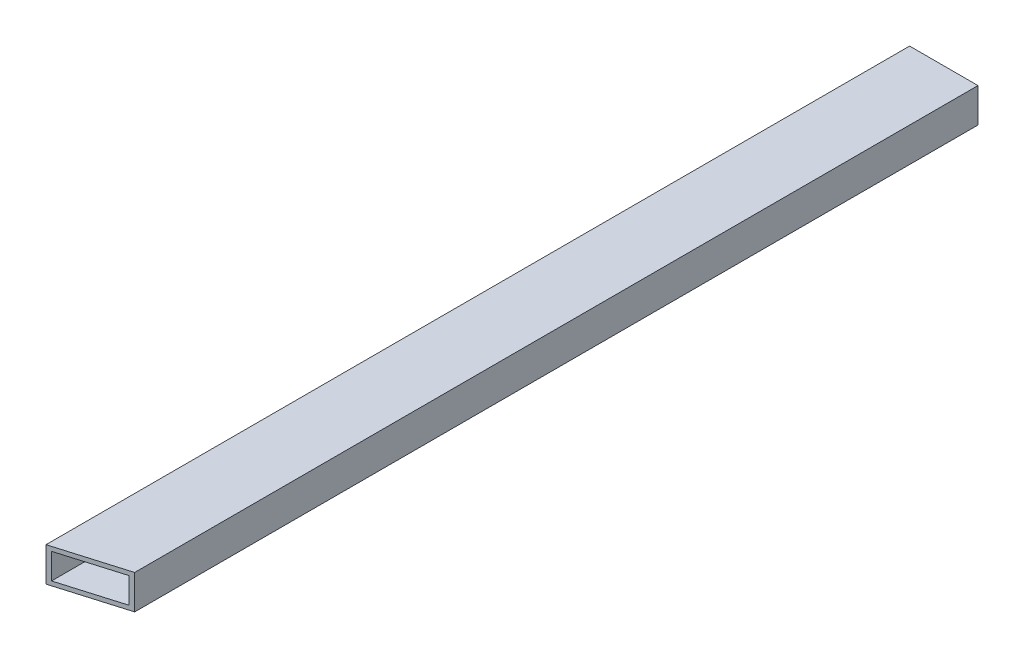
SolidWorks part; units mm, degrees
ref_plane "Front Plane" through (0, 0, 0) normal (0, 0, 1) x (1, 0, 0)
ref_plane "Top Plane" through (0, 0, 0) normal (0, 1, 0) x (1, 0, 0)
ref_plane "Right Plane" through (0, 0, 0) normal (1, 0, 0) x (0, 0, -1)
sketch "Sketch1" plane through (0, 0, 0) normal (0, 0, 1) x (1, 0, 0)
  line L0 (-22.225, 9.525) -> (22.225, 9.525)
  line L2 (-25.4, 12.7) -> (25.4, 12.7)
  line L3 (-25.4, 12.7) -> (-25.4, -12.7)
  line L4 (-25.4, -12.7) -> (25.4, -12.7)
  line L5 (25.4, 12.7) -> (25.4, -12.7)
  line L10 (22.225, 9.525) -> (22.225, -9.525)
  line L11 (-22.225, -9.525) -> (22.225, -9.525)
  line L12 (-22.225, 9.525) -> (-22.225, -9.525)
  point P12 (0, 12.7)
  point P14 (25.4, 0)
  dimension "Wall Thickness" = 3.175
  dimension "Outside Width" = 50.8
  dimension "Outside Height" = 25.4
  dimension "Inside Height" = 19.05
  dimension "Inside Width" = 44.45
sketch "Sketch2" plane through (0, 0, 0) normal (1, 0, 0) x (0, 0, -1)
  line L0 (320.675, 0) -> (-320.675, 0)
  point P4 (0, 0)
  point P7 (-320.675, 0)
  point P10 (320.675, 0)
  dimension "Length" = 641.35
sketch "Sketch3" plane through (0, 0, 0) normal (0, 0, 1) x (1, 0, 0)
  line L21 (25.4, 12.7) -> (-25.4, 12.7)
  line L22 (25.4, -12.7) -> (25.4, 12.7)
  line L23 (-25.4, -12.7) -> (25.4, -12.7)
  line L24 (-25.4, 12.7) -> (-25.4, -12.7)
  line L25 (25.4, 12.7) -> (-25.4, 12.7)
  line L26 (25.4, -12.7) -> (25.4, 12.7)
  line L27 (-25.4, -12.7) -> (25.4, -12.7)
  line L28 (-25.4, 12.7) -> (-25.4, -12.7)
  line L29 (22.225, 9.525) -> (-22.225, 9.525)
  line L30 (22.225, -9.525) -> (22.225, 9.525)
  line L31 (-22.225, -9.525) -> (22.225, -9.525)
  line L32 (-22.225, 9.525) -> (-22.225, -9.525)
  line L33 (22.225, 9.525) -> (-22.225, 9.525)
  line L34 (22.225, -9.525) -> (22.225, 9.525)
  line L35 (-22.225, -9.525) -> (22.225, -9.525)
  line L36 (-22.225, 9.525) -> (-22.225, -9.525)
  dimension "D1" = 0
  dimension "D2" = 0
extrude "Boss-Extrude1" add sketch "Sketch3" along normal up to vertex (320.675 mm away) and the other way up to vertex (320.675 mm away) up to point (0, 0, 320.675) other way up to point (0, 0, -320.675)
sketch "Drawing Reference" plane through (0, 0, 0) normal (1, 0, 0) x (0, 0, -1)
  line L0 (-320.675, 0) -> (320.675, 0) construction
  line L1 (0, -12.7) -> (0, 12.7) construction
  line L2 (-320.675, -12.7) -> (320.675, -12.7) construction
  line L5 (-320.675, 12.7) -> (320.675, 12.7) construction
  point P7 (-284.099, 0)
  point P8 (284.099, 0)
  dimension "D1" = 36.576
sketch "Sketch4" plane through (0, 12.7, 0) normal (0, 1, 0) x (1, 0, 0)
  line L0 (-25.4, -320.675) -> (25.4, -305.6274)
  line L1 (25.4, -320.675) -> (25.4, 320.675) construction
  line L2 (25.4, -320.675) -> (-25.4, -320.675)
  dimension "D1" = 16.5
extrude "Cut-Extrude1" cut sketch "Sketch4" against normal through all and the other way through all flip side to cut
equation "\"D1@Drawing Reference\"=\"Outside Width@Sketch1\" * 0.72"
